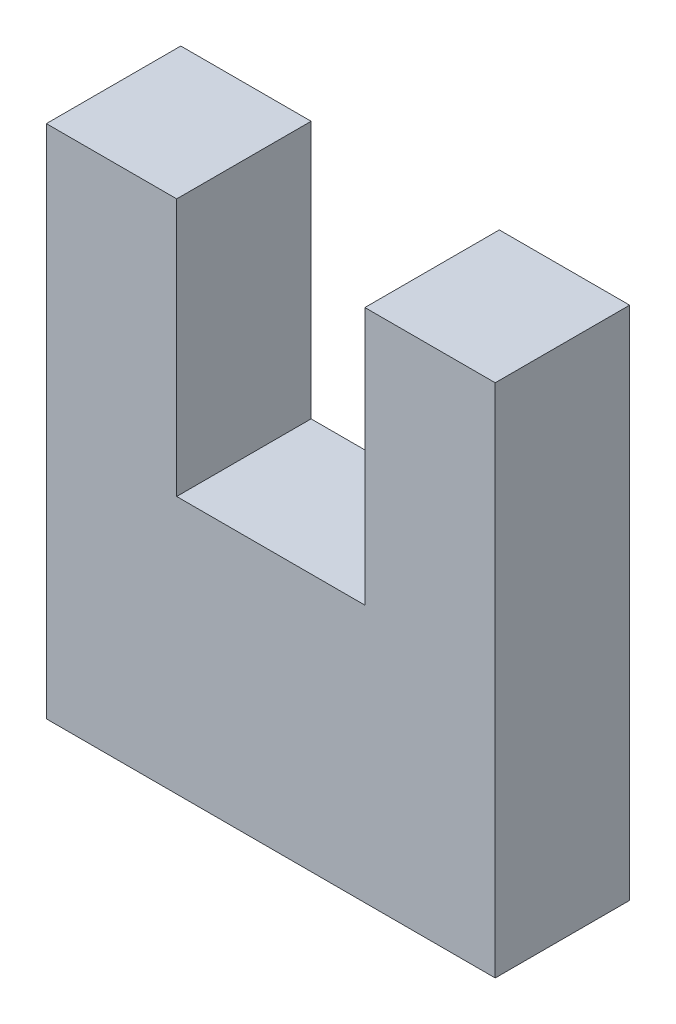
SolidWorks part; units mm, degrees
ref_plane "Front Plane" through (0, 0, 0) normal (0, 0, 1) x (1, 0, 0)
ref_plane "Top Plane" through (0, 0, 0) normal (0, 1, 0) x (1, 0, 0)
ref_plane "Right Plane" through (0, 0, 0) normal (1, 0, 0) x (0, 0, -1)
sketch "Sketch1" plane through (0, 0, 0) normal (0, 1, 0) x (1, 0, 0)
  line L1 (0, 0) -> (29.2608, 0)
  line L2 (0, 0) -> (0, 8.763)
  line L3 (0, 8.763) -> (29.2608, 8.763)
  line L4 (29.2608, 0) -> (29.2608, 8.763)
  dimension "D1" = 29.2608
  dimension "D2" = 8.763
extrude "Boss-Extrude2" add sketch "Sketch1" along normal blind 16.8021
sketch "Sketch2" plane through (0, 16.8021, 0) normal (0, 1, 0) x (1, 0, 0)
  line L0 (8.4963, 8.763) -> (8.4963, 0) construction
  line L1 (29.2608, 8.763) -> (0, 8.763) construction
  line L2 (0, 0) -> (29.2608, 0) construction
  line L3 (0, 8.763) -> (0, 0) construction
  line L4 (20.7645, 8.763) -> (20.7645, 0) construction
  line L5 (29.2608, 0) -> (29.2608, 8.763) construction
  line L7 (0, 8.763) -> (8.4963, 8.763)
  line L8 (0, 8.763) -> (0, 0)
  line L9 (0, 0) -> (8.4963, 0)
  line L10 (8.4963, 8.763) -> (8.4963, 0)
  line L11 (29.2608, 8.763) -> (20.7645, 8.763)
  line L12 (29.2608, 8.763) -> (29.2608, 0)
  line L13 (29.2608, 0) -> (20.7645, 0)
  line L14 (20.7645, 8.763) -> (20.7645, 0)
  dimension "D1" = 8.4963
  dimension "D2" = 8.4963
extrude "Boss-Extrude3" add sketch "Sketch2" along normal blind 16.8021
